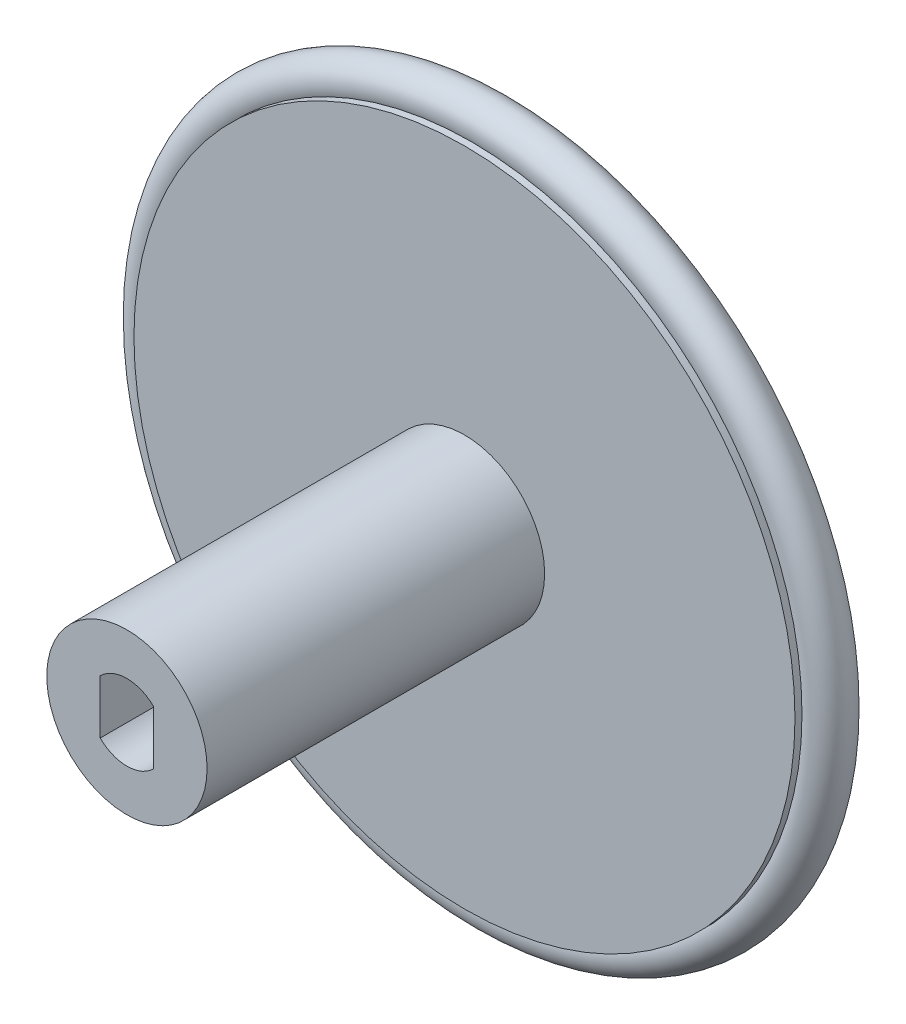
SolidWorks part; units mm, degrees
ref_plane "Alzado" through (0, 0, 0) normal (0, 0, 1) x (1, 0, 0)
ref_plane "Planta" through (0, 0, 0) normal (0, 1, 0) x (1, 0, 0)
ref_plane "Vista lateral" through (0, 0, 0) normal (1, 0, 0) x (0, 0, -1)
sketch "Croquis1" plane through (0, 0, 0) normal (1, 0, 0) x (0, 0, -1)
  line L0 (6.2271, 0) -> (-6.2271, 0) construction
  line L1 (0, 21.5) -> (0, -21.5) construction
  line L2 (-1.9, 0) -> (-1.9, 23.5)
  line L3 (-1.9, 23.5) -> (-1.4, 23.5)
  line L4 (-1.4, 23.5) -> (-0.5, 21.0002)
  line L5 (-0.5, 21.0002) -> (0.5, 21.0002)
  line L6 (1.4, 23.5) -> (0.5, 21.0002)
  line L7 (1.9, 23.5) -> (1.4, 23.5)
  line L8 (1.9, 0) -> (1.9, 23.5)
  line L9 (-1.9, 0) -> (1.9, 0)
  point P4 (0, 0)
  point P8 (0, 0)
  point P18 (0, 21.0002)
  dimension "D1" = 47
  dimension "D2" = 3.8
  dimension "D3" = 19.8
  dimension "D4" = 1
  dimension "D5" = 0.5
  dimension "D6" = 2.6569
revolve "Revolución1" add sketch "Croquis1" angle 360 about L0
sketch "Croquis3" plane through (0, 0, 1.9) normal (0, 0, 1) x (1, 0, 0)
  line L1 (-1.9, 1.9183) -> (1.9, 1.9183) construction
  line L2 (-1.9, 1.9183) -> (-1.9, -1.9183)
  line L3 (-1.9, -1.9183) -> (1.9, -1.9183) construction
  line L4 (1.9, 1.9183) -> (1.9, -1.9183)
  line L5 (-1.9, 1.9183) -> (1.9, -1.9183) construction
  line L6 (-1.9, -1.9183) -> (1.9, 1.9183) construction
  circle A0 centre (0, 0) radius 2.7 construction
  arc A1 (-1.9, 1.9183) -> (1.9, 1.9183) centre (0, 0) cw
  arc A2 (-1.9, -1.9183) -> (1.9, -1.9183) centre (0, 0) ccw
  circle A3 centre (0, 0) radius 5.7
  dimension "D1" = 5.4
  dimension "D4" = 11.4
  dimension "D2" = 3.8
  dimension "D3" = 3
extrude "Saliente-Extruir2" add sketch "Croquis3" along normal blind 24
sketch "Croquis4" plane through (0, 0, 25.9) normal (0, 0, 1) x (1, 0, 0)
  line L2 (-1.9, 1.9183) -> (-1.9, -1.9183)
  line L3 (1.9, -1.9183) -> (1.9, 1.9183)
  line L4 (-1.9, 1.9183) -> (-1.9, -1.9183)
  line L5 (1.9, -1.9183) -> (1.9, 1.9183)
  arc A2 (-1.9, -1.9183) -> (1.9, -1.9183) centre (0, 0) ccw
  arc A3 (1.9, 1.9183) -> (-1.9, 1.9183) centre (0, 0) ccw
  arc A4 (-1.9, -1.9183) -> (1.9, -1.9183) centre (0, 0) ccw
  arc A5 (1.9, 1.9183) -> (-1.9, 1.9183) centre (0, 0) ccw
  dimension "D1" = 0
extrude "Saliente-Extruir3" add sketch "Croquis4" against normal up to next from offset 5 offset against normal yes
sketch "Croquis5" plane through (0, 0, 0) normal (1, 0, 0) x (0, 0, -1)
  line L0 (-0.5, 21.0002) -> (-1.4, 23.5) construction
  line L1 (-9.0932, 0) -> (9.0932, 0) construction
  circle A0 centre (0, 24.0396) radius 1.5
  point P9 (0, 0)
  dimension "D1" = 3
revolve "Revolución2" add sketch "Croquis5" angle 360 about L1
